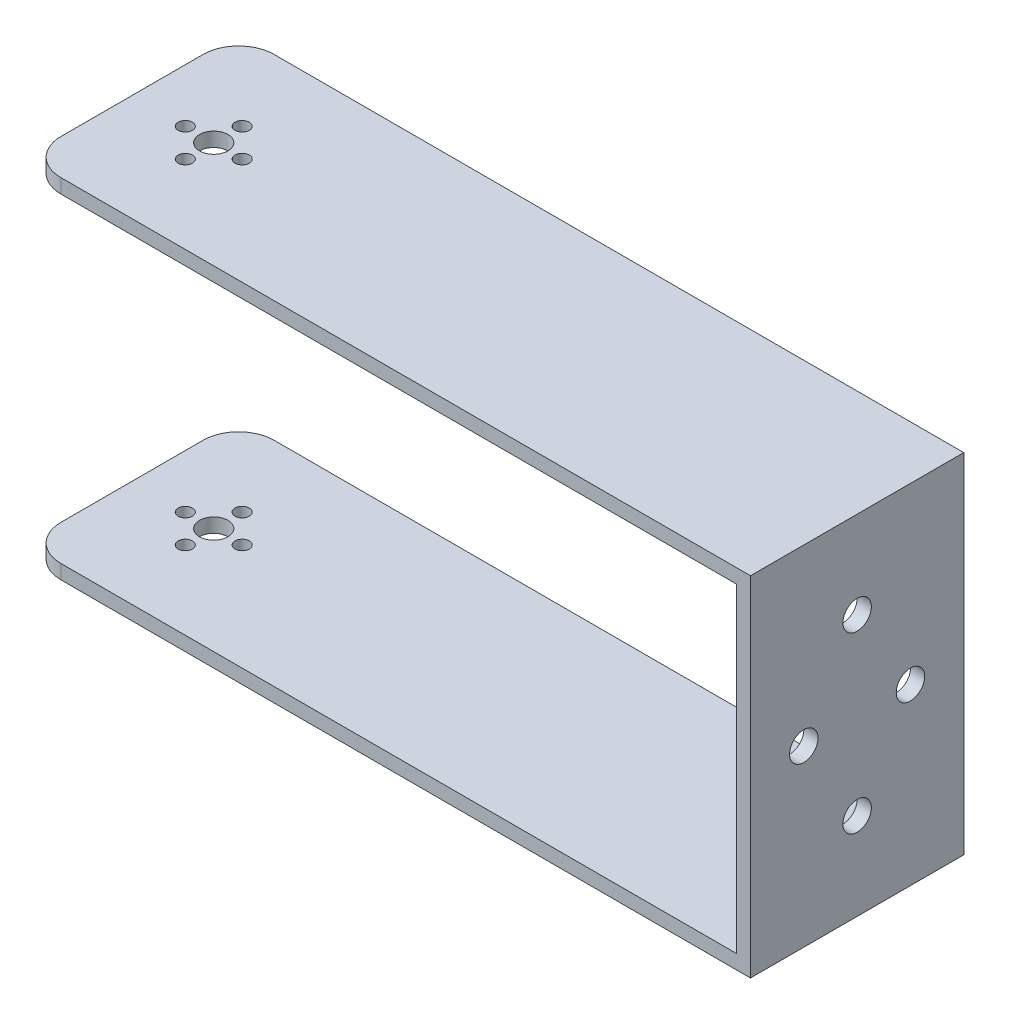
SolidWorks part; units mm, degrees
ref_plane "Ön Düzlem" through (0, 0, 0) normal (0, 0, 1) x (1, 0, 0)
ref_plane "Üst Düzlem" through (0, 0, 0) normal (0, 1, 0) x (1, 0, 0)
ref_plane "Sağ Düzlem" through (0, 0, 0) normal (1, 0, 0) x (0, 0, -1)
sketch "Çizim1" plane through (0, 0, 0) normal (0, 0, 1) x (1, 0, 0)
  line L0 (0, 0) -> (200, 0)
  line L1 (200, 0) -> (200, 90)
  line L2 (200, 90) -> (0, 90)
  dimension "D1" = 90
  dimension "D2" = 200
extrude "Ekstrüzyon-İnce1" add sketch "Çizim1" along normal blind 60 thin
fillet "Radyus1" radius 10 4 edges at (0, -2, 60) (0, -2, 0) (0, 92, 0) (0, 92, 60)
sketch "Çizim2" plane through (0, 94, 0) normal (0, 1, 0) x (1, 0, 0)
  line L0 (0, -50) -> (0, -10) construction
  circle A0 centre (23, -30) radius 4
  circle A1 centre (23, -22) radius 2
  circle A2 centre (23, -38) radius 2
  circle A3 centre (31, -30) radius 2
  circle A4 centre (15, -30) radius 2
  dimension "D1" = 8
  dimension "D3" = 4
  dimension "D5" = 4
  dimension "D6" = 15
  dimension "D7" = 8
  dimension "D8" = 8
  dimension "D9" = 4
  dimension "D4" = 8
  dimension "D2" = 8
  dimension "D10" = 4
  dimension "D11" = 8
extrude "Kes-Ekstrüzyon1" cut sketch "Çizim2" against normal up to next
ref_plane "Düzlem1" through (0, 45, 0) normal (0, 1, 0) x (1, 0, 0)
mirror "Aynalama1" about plane through (0, 45, 0) normal (0, 1, 0) of "Kes-Ekstrüzyon1"
sketch "Çizim3" plane through (204, 0, 0) normal (1, 0, 0) x (0, 0, -1)
  line L0 (-60, -4) -> (-60, 94) construction
  line L3 (-60, -4) -> (0, -4) construction
  line L6 (-60, 94) -> (0, 94) construction
  line L7 (0, -4) -> (0, 94) construction
  circle A0 centre (-30, 69.5) radius 4
  circle A1 centre (-45, 45) radius 4
  circle A2 centre (-15, 45) radius 4
  circle A3 centre (-30, 20.5) radius 4
  dimension "D1" = 8
  dimension "D2" = 8
  dimension "D3" = 30
  dimension "D4" = 15
  dimension "D5" = 49
  dimension "D6" = 24.5
  dimension "D7" = 24.5
  dimension "D8" = 15
  dimension "D9" = 8
  dimension "D10" = 8
extrude "Kes-Ekstrüzyon2" cut sketch "Çizim3" against normal up to next
